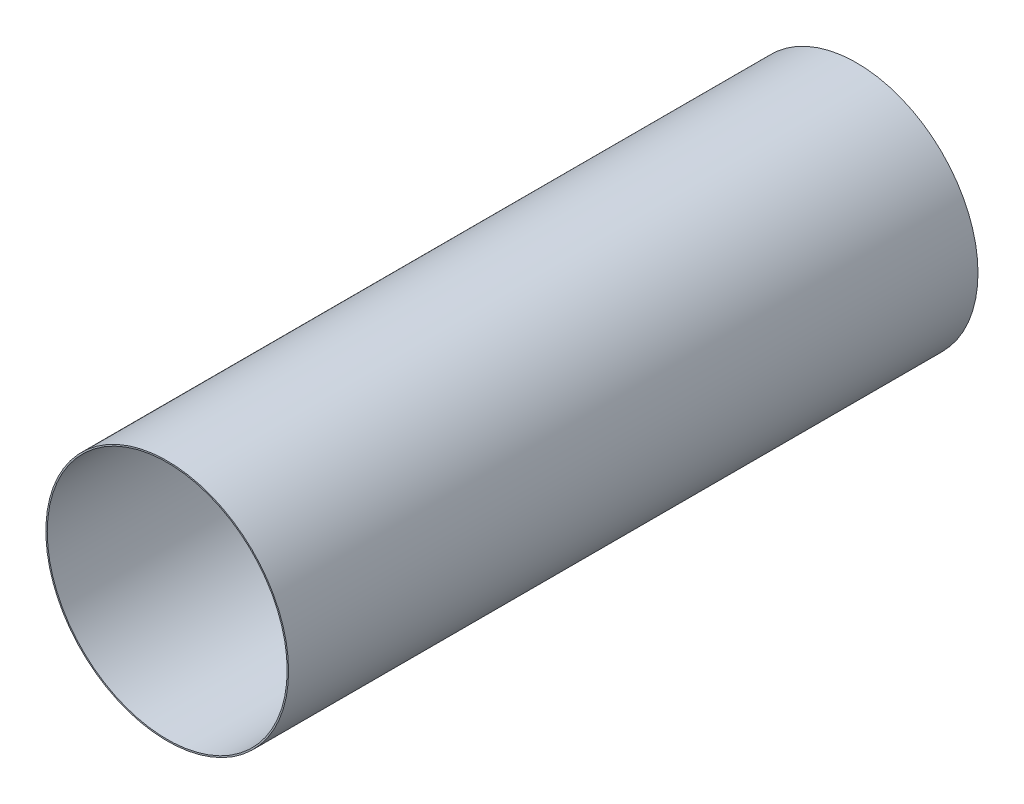
SolidWorks part; units mm, degrees
ref_plane "Front Plane" through (0, 0, 0) normal (0, 0, 1) x (1, 0, 0)
ref_plane "Top Plane" through (0, 0, 0) normal (0, 1, 0) x (1, 0, 0)
ref_plane "Right Plane" through (0, 0, 0) normal (1, 0, 0) x (0, 0, -1)
sketch "Sketch1" plane through (0, 0, 0) normal (0, 0, 1) x (1, 0, 0)
  circle A0 centre (0, 0) radius 2105.5785
  circle A1 centre (0, 0) radius 2130.0235
  dimension "D1" = 4211.157
  dimension "D2" = 4260.047
extrude "Boss-Extrude1" add sketch "Sketch1" against normal blind 12100
